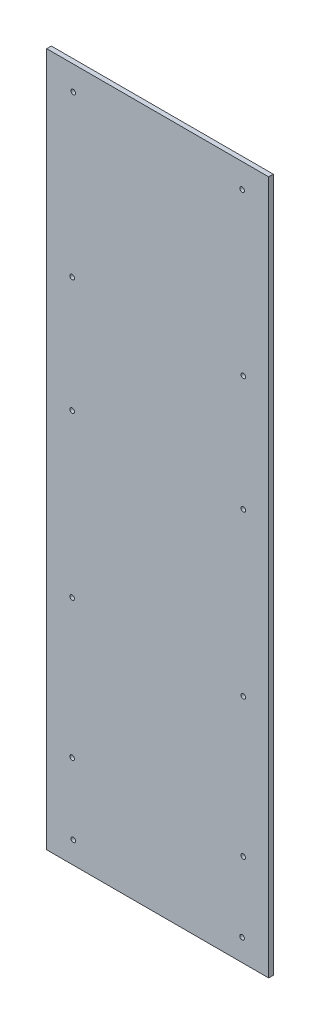
SolidWorks part; units mm, degrees
material "Alumina"
ref_plane "Front Plane" through (0, 0, 0) normal (0, 0, 1) x (1, 0, 0)
ref_plane "Top Plane" through (0, 0, 0) normal (0, 1, 0) x (1, 0, 0)
ref_plane "Right Plane" through (0, 0, 0) normal (1, 0, 0) x (0, 0, -1)
sketch "Sketch1" plane through (0, 0, 0) normal (0, 0, 1) x (1, 0, 0)
  line L1 (48, -150) -> (-48, -150)
  line L2 (48, -150) -> (48, 150)
  line L3 (48, 150) -> (-48, 150)
  line L4 (-48, -150) -> (-48, 150)
  line L5 (48, -150) -> (-48, 150) construction
  line L6 (48, 150) -> (-48, -150) construction
  point P0 (0, 0)
  dimension "D1" = 96
  dimension "D2" = 300
extrude "Boss-Extrude1" add sketch "Sketch1" along normal blind 2
sketch "Sketch2" plane through (0, 0, 2) normal (0, 0, 1) x (1, 0, 0)
  line L0 (-48, 150) -> (-48, -150) construction
  line L1 (48, 150) -> (-48, 150) construction
  line L3 (0, -1.1) -> (0, 1.1) construction
  line L5 (-37, 20) -> (-37, -110) construction
  circle A0 centre (-37, 70) radius 1
  circle A1 centre (-37, 20) radius 1
  circle A22 centre (-37, -110) radius 1
  circle A23 centre (-37, -50) radius 1
  circle A24 centre (37, 70) radius 1
  circle A25 centre (37, 20) radius 1
  circle A26 centre (37, -50) radius 1
  circle A27 centre (37, -110) radius 1
  point P9 (0, 0)
  point P20 (33, -124)
  dimension "D1" = 2
  dimension "D3" = 80
  dimension "D4" = 2
  dimension "D6" = 11
  dimension "D15" = 2
  dimension "D19" = 2
  dimension "D20" = 60
  dimension "D7" = 70
  dimension "D2" = 11
  dimension "D5" = 50
extrude "Cut-Extrude1" cut sketch "Sketch2" against normal blind 10
sketch "Sketch3" plane through (0, 0, 2) normal (0, 0, 1) x (1, 0, 0)
  line L0 (-36.5, 139.5) -> (36.5, 139.5) construction
  line L1 (36.5, 139.5) -> (36.5, -140.5) construction
  line L2 (36.5, -140.5) -> (-36.5, -140.5) construction
  line L3 (-36.5, -140.5) -> (-36.5, 139.5) construction
  line L4 (-48, 150) -> (-48, -150) construction
  line L5 (48, -150) -> (48, 150) construction
  line L6 (48, 150) -> (-48, 150) construction
  line L7 (-48, -150) -> (48, -150) construction
  circle A0 centre (-36.5, 139.5) radius 1
  circle A1 centre (36.5, 139.5) radius 1
  circle A2 centre (-36.5, -140.5) radius 1
  circle A3 centre (36.5, -140.5) radius 1
  dimension "D5" = 2
  dimension "D6" = 2
  dimension "D7" = 2
  dimension "D8" = 2
  dimension "D1" = 11.5
  dimension "D2" = 11.5
  dimension "D3" = 10.5
  dimension "D4" = 9.5
extrude "Cut-Extrude2" cut sketch "Sketch3" against normal blind 10
